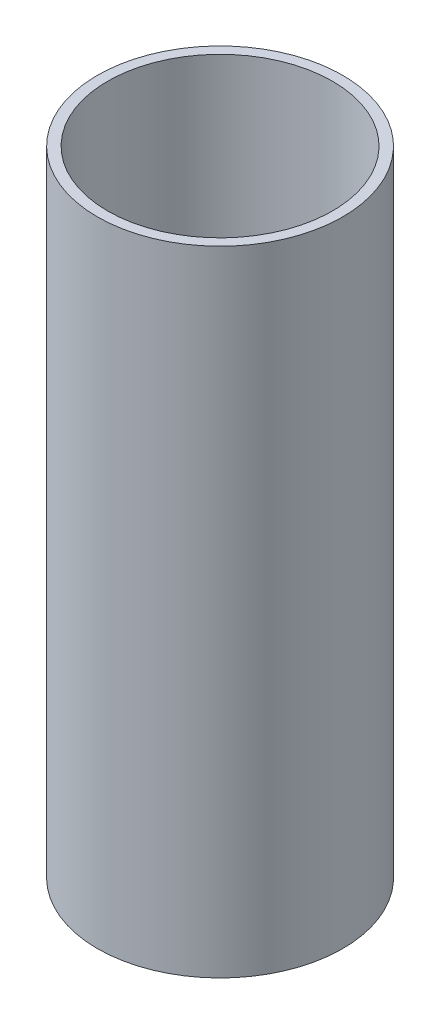
SolidWorks part; units mm, degrees
ref_plane "Front Plane" through (0, 0, 0) normal (0, 0, 1) x (1, 0, 0)
ref_plane "Top Plane" through (0, 0, 0) normal (0, 1, 0) x (1, 0, 0)
ref_plane "Right Plane" through (0, 0, 0) normal (1, 0, 0) x (0, 0, -1)
sketch "Sketch1" plane through (0, 0, 0) normal (0, 1, 0) x (1, 0, 0)
  circle A0 centre (0.7019, 0) radius 19.05
  dimension "D1" = 38.1
extrude "Boss-Extrude1" add sketch "Sketch1" along normal blind 98.425
sketch "Sketch2" plane through (0, 98.425, 0) normal (0, 1, 0) x (1, 0, 0)
  line L0 (0, 19.0371) -> (1.4038, -19.0371) construction
  line L1 (-18.3481, 0) -> (19.7519, 0) construction
  circle A0 centre (0.7019, 0) radius 19.05 construction
  circle A3 centre (0.7019, 0) radius 17.4625
  dimension "D1" = 34.925
extrude "Cut-Extrude1" cut sketch "Sketch2" against normal blind 69.85
sketch "Sketch3" plane through (0, 28.575, 0) normal (0, 1, 0) x (1, 0, 0)
  line L0 (0.7019, 17.4625) -> (0.7019, -17.4625) construction
  line L1 (-16.7606, 0) -> (18.1644, 0) construction
  circle A0 centre (0.7019, 0) radius 17.4625 construction
  circle A1 centre (0.7019, 0) radius 17.4625 construction
  circle A2 centre (0.7019, 0) radius 11.1125
  dimension "D1" = 22.225
extrude "Cut-Extrude2" cut sketch "Sketch3" against normal blind 25.4
